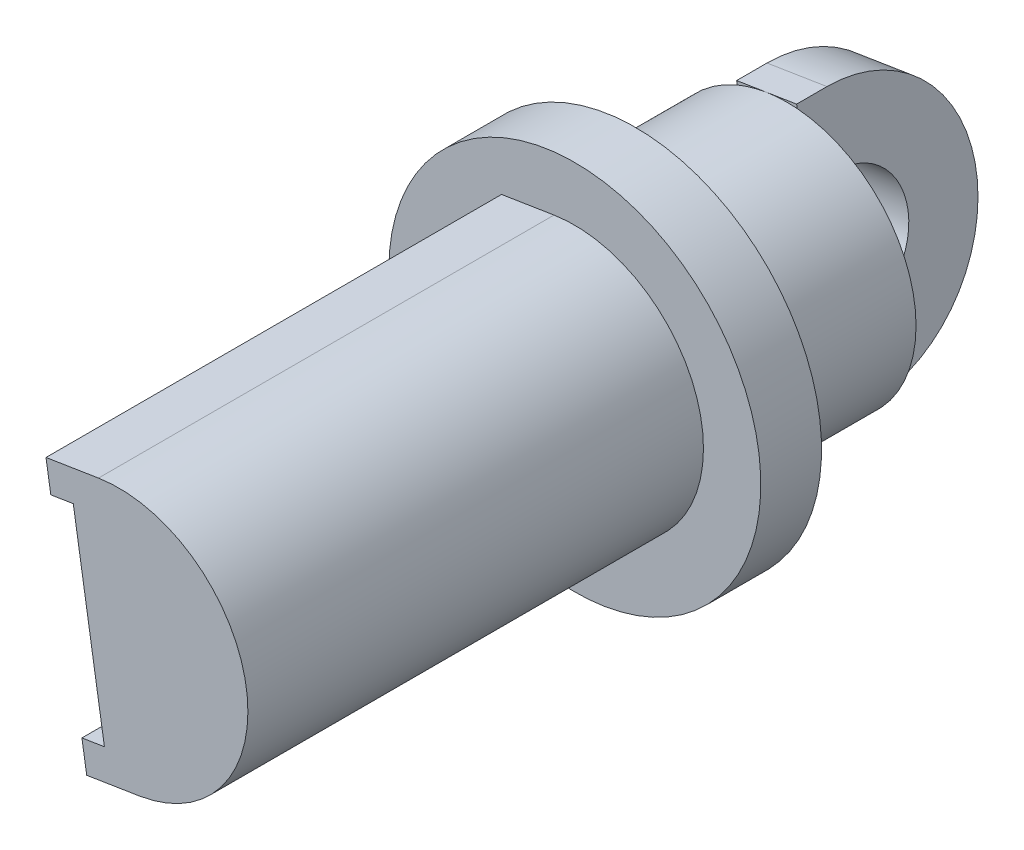
SolidWorks part; units mm, degrees
ref_plane "Alzado" through (0, 0, 0) normal (0, 0, 1) x (1, 0, 0)
ref_plane "Planta" through (0, 0, 0) normal (0, 1, 0) x (1, 0, 0)
ref_plane "Vista lateral" through (0, 0, 0) normal (1, 0, 0) x (0, 0, -1)
ref_plane "Plano1" through (-45.5919, -7.2817, 0) normal (-0.9875, -0.1577, 0) x (0.1577, -0.9875, 0)
sketch "Croquis1" plane through (-45.5919, -7.2817, 0) normal (-0.9875, -0.1577, 0) x (0.1577, -0.9875, 0)
  line L0 (51.0411, 0) -> (42.5411, 0)
  line L1 (42.5411, 0) -> (42.5411, -1)
  line L2 (51.0411, -1) -> (51.0411, 0)
  arc A0 (42.5411, -1) -> (51.0411, -1) centre (46.7911, -1) ccw
extrude "Saliente-Extruir1" add sketch "Croquis1" against normal blind 2
hole_wizard "Diámetro de taladro Ø4.0 (4)1" positions "Croquis3" profile "Croquis2" hole size "Ø4.0" standard "Ansi Metric"
sketch "Croquis3" plane through (-43.6169, -6.9663, 0) normal (0.9875, 0.1577, 0) x (0, 0, -1)
  point P0 (1, -46.7911)
sketch "Croquis2" plane through (-36.2372, -53.1717, -1) normal (0, 0, 1) x (-0.1577, 0.9875, 0)
  line L0 (0, 0) -> (0, 3.3238)
  line L1 (0, 3.3238) -> (2, 3.3238)
  line L2 (2, 3.3238) -> (2, 0)
  line L5 (2, 0) -> (0, 0)
  line L11 (0, -6.35) -> (0, 107.95) construction
  dimension "Diámetro de taladro hasta el siguiente" = 4
  dimension "Profundidad de taladro hasta el siguiente" = 3.3238
ref_plane "Plano2" through (0, 0, 0) normal (0, 0, -1) x (-1, 0, 0)
sketch "Croquis4" plane through (0, 0, 0) normal (0, 0, -1) x (-1, 0, 0)
  circle A0 centre (37.2247, -53.3295) radius 4.25
extrude "Saliente-Extruir2" add sketch "Croquis4" against normal blind 7
sketch "Croquis5" plane through (0, 0, 7) normal (0, 0, 1) x (1, 0, 0)
  line L0 (-39.6231, -49.4086) -> (-37.895, -49.1326)
  line L1 (-36.5544, -57.5263) -> (-38.2825, -57.8023)
  line L2 (-38.2825, -57.8023) -> (-39.6231, -49.4086)
  arc A0 (-37.895, -49.1326) -> (-36.5544, -57.5263) centre (-37.2247, -53.3295) cw
  dimension "D1" = 1.75
extrude "Saliente-Extruir3" add sketch "Croquis5" along normal blind 15
sketch "Croquis6" plane through (0, 0, 22) normal (0, 0, 1) x (1, 0, 0)
  line L0 (-38.7247, -50.2778) -> (-39.7122, -50.4356)
  line L1 (-39.7122, -50.4356) -> (-38.6871, -56.8542)
  line L2 (-38.6871, -56.8542) -> (-37.6996, -56.6965)
  line L3 (-37.6996, -56.6965) -> (-38.7247, -50.2778)
  dimension "D1" = 1
extrude "Cortar-Extruir1" cut sketch "Croquis6" against normal blind 15
sketch "Croquis7" plane through (0, 0, 7) normal (0, 0, -1) x (-1, 0, 0)
  circle A0 centre (37.211, -53.4153) radius 6.125
  dimension "D1" = 12.25
extrude "Saliente-Extruir4" add sketch "Croquis7" along normal blind 2
